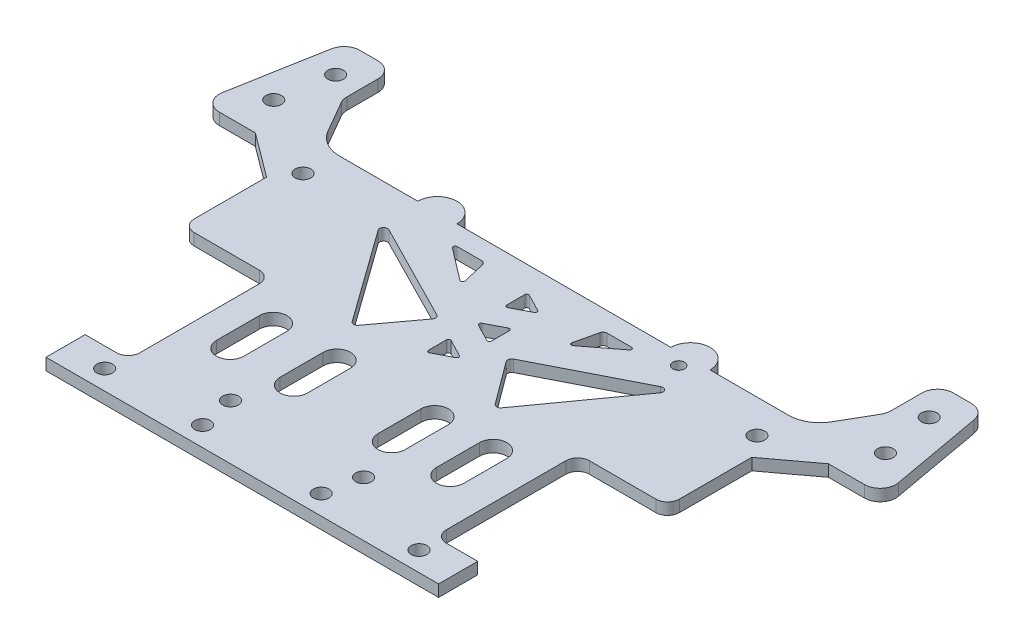
SolidWorks part; units mm, degrees
ref_plane "前视基准面" through (0, 0, 0) normal (0, 0, 1) x (1, 0, 0)
ref_plane "上视基准面" through (0, 0, 0) normal (0, 1, 0) x (1, 0, 0)
ref_plane "右视基准面" through (0, 0, 0) normal (1, 0, 0) x (0, 0, -1)
other "Configuration Table"
sketch "草图1" plane through (0, 0, 0) normal (0, 1, 0) x (1, 0, 0)
  line L0 (0, -16.9729) -> (0, 16.9729) construction
  line L1 (2, 16.9729) -> (2, -16.9729) construction
  line L3 (-2, 16.3622) -> (-2, -16.9729) construction
  point P3 (0, 0)
  dimension "D1" = 2
  dimension "D2" = 2
sketch "草图2" plane through (0, 0, 0) normal (0, 1, 0) x (1, 0, 0)
  line L0 (335.3431, 5) -> (-235.3431, 5) construction
  line L1 (-50, 0) -> (50, 0)
  line L2 (0, 0) -> (0, 19.5248) construction
  line L3 (42, 10) -> (50, 10)
  line L4 (50, 0) -> (50, 10)
  line L6 (0, 19.5248) -> (0, 40.19) construction
  line L8 (39, 13) -> (39, 43.53)
  line L9 (42, 46.53) -> (59, 46.53)
  line L10 (0, 40.19) -> (0, 82.03) construction
  line L11 (-57.3812, 82.03) -> (-37.34, 82.03)
  line L12 (62, 49.53) -> (62, 68.03)
  line L13 (64.3094, 86.03) -> (68.9641, 94.0922)
  line L14 (69.5, 96.0922) -> (69.5, 104.0204)
  line L17 (73.5, 108.0204) -> (78.1587, 108.0204)
  line L19 (82.0948, 104.7324) -> (86.3672, 81.1158)
  line L20 (62, 68.03) -> (73.2197, 76.4037)
  line L21 (73.2197, 76.4037) -> (82.4311, 76.4037)
  line L22 (12.5, 25.5) -> (12.5, 36.5) construction
  line L23 (9, 25.5) -> (9, 36.5)
  line L24 (16, 25.5) -> (16, 36.5)
  line L25 (-73.5, 108.0204) -> (-78.1587, 108.0204)
  line L26 (-69.5, 96.0922) -> (-69.5, 104.0204)
  line L27 (-64.3094, 86.03) -> (-68.9641, 94.0922)
  line L29 (-42.32, 10) -> (-50.32, 10)
  line L30 (-39.32, 13) -> (-39.32, 43.53)
  line L31 (-42.32, 46.53) -> (-59, 46.53)
  line L32 (-62, 49.53) -> (-62, 68.03)
  line L33 (-62, 68.03) -> (-73.2197, 76.4037)
  line L34 (-73.2197, 76.4037) -> (-82.4311, 76.4037)
  line L35 (-82.0948, 104.7324) -> (-86.3672, 81.1158)
  line L36 (-12.5, 25.5) -> (-12.5, 36.5) construction
  line L37 (-9, 25.5) -> (-9, 36.5)
  line L38 (-16, 25.5) -> (-16, 36.5)
  line L39 (-50.32, 10) -> (-50.32, 0)
  line L40 (-50, 0) -> (-50.32, 0)
  line L41 (-28.772, 36.5) -> (-28.772, 25.5) construction
  line L42 (-25.272, 36.5) -> (-25.272, 25.5)
  line L43 (-32.272, 36.5) -> (-32.272, 25.5)
  line L45 (27.4578, 36.5) -> (27.4578, 25.5) construction
  line L46 (30.9578, 36.5) -> (30.9578, 25.5)
  line L47 (23.9578, 36.5) -> (23.9578, 25.5)
  line L60 (-34.7339, 72.03) -> (-9.7834, 59.3228)
  line L61 (-9.4337, 57.8365) -> (-17.4687, 46.9881)
  line L62 (-19.0845, 47) -> (-36, 70.5556)
  line L63 (-22.2986, 77.03) -> (-15.9986, 77.03)
  line L64 (-15.0247, 76.2572) -> (-13.6616, 70.4141)
  line L65 (-14.4522, 69.9032) -> (-22.6022, 76.1328)
  line L66 (9.4337, 57.8365) -> (17.4687, 46.9881)
  line L67 (19.0845, 47) -> (36, 70.5556)
  line L68 (34.7339, 72.03) -> (9.7834, 59.3228)
  line L69 (14.4522, 69.9032) -> (22.6022, 76.1328)
  line L70 (15.0247, 76.2572) -> (13.6616, 70.4141)
  line L71 (22.2986, 77.03) -> (15.9986, 77.03)
  line L72 (-3.0133, 75.03) -> (-3.0133, 70.43)
  line L73 (-2.2833, 69.986) -> (2.1563, 72.286)
  line L74 (2.1563, 73.174) -> (-2.2833, 75.474)
  line L75 (3.0133, 65.0858) -> (3.0133, 60.4858)
  line L76 (2.2833, 60.0419) -> (-2.1563, 62.3419)
  line L77 (-2.1563, 63.2298) -> (2.2833, 65.5298)
  line L81 (-2.2833, 49.986) -> (2.1563, 52.286)
  line L82 (-3.0133, 55.03) -> (-3.0133, 50.43)
  line L83 (2.1563, 53.174) -> (-2.2833, 55.474)
  line L84 (32.34, 79) -> (32.34, 82.03) construction
  line L87 (-27.34, 82.03) -> (27.34, 82.03)
  line L88 (37.34, 82.03) -> (57.3812, 82.03)
  arc A0 (82.4311, 76.4037) -> (86.3672, 81.1158) centre (82.4311, 80.4037) ccw
  arc A1 (82.0948, 104.7324) -> (78.1587, 108.0204) centre (78.1587, 104.0204) ccw
  arc A2 (69.5, 104.0204) -> (73.5, 108.0204) centre (73.5, 104.0204) cw
  arc A3 (68.9641, 94.0922) -> (69.5, 96.0922) centre (65.5, 96.0922) ccw
  arc A4 (64.3094, 86.03) -> (57.3812, 82.03) centre (57.3812, 90.03) cw
  circle A5 centre (40, 5) radius 2
  circle A6 centre (15, 5) radius 2
  circle A7 centre (57.84, 73.5) radius 2
  circle A8 centre (16.84, 14) radius 2
  arc A9 (9, 25.5) -> (16, 25.5) centre (12.5, 25.5) ccw
  arc A10 (16, 36.5) -> (9, 36.5) centre (12.5, 36.5) ccw
  circle A11 centre (78.1587, 86.03) radius 2
  circle A12 centre (75.8293, 99.5272) radius 2
  arc A13 (-69.5, 104.0204) -> (-73.5, 108.0204) centre (-73.5, 104.0204) ccw
  arc A14 (-68.9641, 94.0922) -> (-69.5, 96.0922) centre (-65.5, 96.0922) cw
  arc A15 (-64.3094, 86.03) -> (-57.3812, 82.03) centre (-57.3812, 90.03) ccw
  arc A16 (-82.4311, 76.4037) -> (-86.3672, 81.1158) centre (-82.4311, 80.4037) cw
  arc A17 (-82.0948, 104.7324) -> (-78.1587, 108.0204) centre (-78.1587, 104.0204) cw
  circle A18 centre (-75.8293, 99.5272) radius 2
  circle A19 centre (-78.1587, 86.03) radius 2
  circle A20 centre (-58.16, 73.5) radius 2
  circle A21 centre (-40.32, 5) radius 2
  circle A22 centre (-15.32, 5) radius 2
  arc A24 (-9, 25.5) -> (-16, 25.5) centre (-12.5, 25.5) cw
  arc A25 (-16, 36.5) -> (-9, 36.5) centre (-12.5, 36.5) cw
  circle A26 centre (-17.16, 14) radius 2
  arc A27 (-59, 46.53) -> (-62, 49.53) centre (-59, 49.53) cw
  arc A28 (-39.32, 13) -> (-42.32, 10) centre (-42.32, 13) cw
  arc A29 (-42.32, 46.53) -> (-39.32, 43.53) centre (-42.32, 43.53) cw
  arc A30 (39, 43.53) -> (42, 46.53) centre (42, 43.53) cw
  arc A31 (59, 46.53) -> (62, 49.53) centre (59, 49.53) ccw
  arc A32 (42, 10) -> (39, 13) centre (42, 13) cw
  arc A33 (-25.272, 36.5) -> (-32.272, 36.5) centre (-28.772, 36.5) ccw
  arc A34 (-32.272, 25.5) -> (-25.272, 25.5) centre (-28.772, 25.5) ccw
  arc A35 (30.9578, 36.5) -> (23.9578, 36.5) centre (27.4578, 36.5) ccw
  arc A36 (23.9578, 25.5) -> (30.9578, 25.5) centre (27.4578, 25.5) ccw
  arc A37 (-34.7339, 72.03) -> (-36, 70.5556) centre (-35.1877, 71.1389) ccw
  arc A38 (-9.7834, 59.3228) -> (-9.4337, 57.8365) centre (-10.2372, 58.4317) cw
  arc A39 (-17.4687, 46.9881) -> (-19.0845, 47) centre (-18.2723, 47.5833) cw
  arc A40 (-15.9986, 77.03) -> (-15.0247, 76.2572) centre (-15.9986, 76.03) cw
  arc A41 (-22.2986, 77.03) -> (-22.6022, 76.1328) centre (-22.2986, 76.53) ccw
  arc A42 (-13.6616, 70.4141) -> (-14.4522, 69.9032) centre (-14.1486, 70.3005) cw
  arc A43 (9.7834, 59.3228) -> (9.4337, 57.8365) centre (10.2372, 58.4317) ccw
  arc A44 (17.4687, 46.9881) -> (19.0845, 47) centre (18.2723, 47.5833) ccw
  arc A45 (34.7339, 72.03) -> (36, 70.5556) centre (35.1877, 71.1389) cw
  arc A46 (22.2986, 77.03) -> (22.6022, 76.1328) centre (22.2986, 76.53) cw
  arc A47 (13.6616, 70.4141) -> (14.4522, 69.9032) centre (14.1486, 70.3005) ccw
  arc A48 (15.9986, 77.03) -> (15.0247, 76.2572) centre (15.9986, 76.03) ccw
  arc A49 (2.1563, 52.286) -> (2.1563, 53.174) centre (1.9263, 52.73) ccw
  arc A50 (-2.2833, 49.986) -> (-3.0133, 50.43) centre (-2.5133, 50.43) cw
  arc A51 (-3.0133, 55.03) -> (-2.2833, 55.474) centre (-2.5133, 55.03) cw
  arc A52 (3.0133, 60.4858) -> (2.2833, 60.0419) centre (2.5133, 60.4858) cw
  arc A53 (3.0133, 65.0858) -> (2.2833, 65.5298) centre (2.5133, 65.0858) ccw
  arc A54 (-2.1563, 62.3419) -> (-2.1563, 63.2298) centre (-1.9263, 62.7858) cw
  arc A55 (2.1563, 72.286) -> (2.1563, 73.174) centre (1.9263, 72.73) ccw
  arc A56 (-3.0133, 70.43) -> (-2.2833, 69.986) centre (-2.5133, 70.43) ccw
  arc A57 (-3.0133, 75.03) -> (-2.2833, 75.474) centre (-2.5133, 75.03) cw
  circle A58 centre (32.34, 79) radius 1.5
  arc A59 (27.34, 82.03) -> (37.34, 82.03) centre (32.34, 82.03) cw
  arc A60 (-27.34, 82.03) -> (-37.34, 82.03) centre (-32.34, 82.03) ccw
  point P11 (62, 68.03)
  point P14 (50, 5)
  point P29 (87.2197, 76.4037)
  point P33 (81.5, 108.0204)
  point P36 (69.5, 108.0204)
  point P39 (69.5, 95.0204)
  point P42 (62, 82.03)
  point P44 (12.5, 31)
  point P51 (12.5, 40)
  point P52 (12.5, 22)
  point P57 (-46.32, 10)
  point P58 (-69.5, 100.0563)
  point P64 (75.8293, 108.0204)
  point P79 (-39.32, 10)
  point P101 (-12.5, 31)
  point P111 (39, 46.53)
  point P114 (62, 46.53)
  point P117 (39, 10)
  point P120 (-28.772, 31)
  point P127 (27.4578, 31)
  point P178 (-3.0133, 72.73)
  point P180 (3.0133, 62.7858)
  point P195 (-3.0133, 62.7858)
  point P198 (3.0133, 72.73)
  dimension "D15" = 4
  dimension "D16" = 4
  dimension "D17" = 4
  dimension "D18" = 8
  dimension "D19" = 4
  dimension "D20" = 4
  dimension "D25" = 4
  dimension "D26" = 4
  dimension "D31" = 40
  dimension "D33" = 4
  dimension "D34" = 4
  dimension "D35" = 6.3293
  dimension "D36" = 8.4931
  dimension "D39" = 4
  dimension "D42" = 22.16
  dimension "D47" = 116
  dimension "D48" = 59.5
  dimension "D49" = 4
  dimension "D50" = 5
  dimension "D51" = 4
  dimension "D52" = 35
  dimension "D53" = 5
  dimension "D54" = 10
  dimension "D55" = 4
  dimension "D24" = 59.5
  dimension "D23" = 41
  dimension "D56" = 14
  dimension "D61" = 4
  dimension "D62" = 4
  dimension "D63" = 4
  dimension "D64" = 24
  dimension "D65" = 2.9037
  dimension "D66" = 9.6263
  dimension "D70" = 8
  dimension "D71" = 4
  dimension "D58" = 4
  dimension "D72" = 4
  dimension "D74" = 8.4931
  dimension "D67" = 8.6587
  dimension "D73" = 6.3293
  dimension "D75" = 3
  dimension "D76" = 3
  dimension "D77" = 3
  dimension "D80" = 11.5
  dimension "D81" = 22.5
  dimension "D85" = 25.5
  dimension "D86" = 1
  dimension "D87" = 1
  dimension "D88" = 1
  dimension "D89" = 1
  dimension "D90" = 0.5
  dimension "D91" = 0.5
  dimension "D92" = 0.5
  dimension "D109" = 3
  dimension "D112" = 5
  dimension "D1" = 50
  dimension "D2" = 10
  dimension "D3" = 36.53
  dimension "D4" = 39
  dimension "D5" = 62
  dimension "D6" = 35.5
  dimension "D7" = 14
  dimension "D8" = 15
  dimension "D9" = 14
  dimension "D10" = 14
  dimension "D11" = 60
  dimension "D12" = 15
  dimension "D13" = 13
  dimension "D14" = 12
  dimension "D21" = 10
  dimension "D22" = 24
  dimension "D27" = 4
  dimension "D28" = 22.16
  dimension "D29" = 30
  dimension "D30" = 23
  dimension "D32" = 22
  dimension "D37" = 9.6263
  dimension "D38" = 8.6587
  dimension "D40" = 34
  dimension "D41" = 14
  dimension "D43" = 36.53
  dimension "D44" = 124
  dimension "D45" = 11
  dimension "D46" = 10
  dimension "D57" = 9.2114
  dimension "D59" = 4.6587
  dimension "D60" = 7.9282
  dimension "D68" = 60
  dimension "D69" = 9.3094
  dimension "D78" = 25
  dimension "D79" = 8.16
  dimension "D82" = 31
  dimension "D83" = 8.0422
  dimension "D84" = 14.048
  dimension "D93" = 6.3
  dimension "D94" = 8.15
  dimension "D95" = 13.6616
  dimension "D96" = 5
  dimension "D97" = 10.2581
  dimension "D98" = 29
  dimension "D99" = 28
  dimension "D100" = 13.5
  dimension "D101" = 10
  dimension "D102" = 26
  dimension "D103" = 47
  dimension "D104" = 4.6
  dimension "D105" = 5
  dimension "D106" = 7
  dimension "D107" = 18.8002
  dimension "D108" = 27
  dimension "D110" = 25.5
  dimension "D111" = 5.5
extrude "凸台-拉伸2" add sketch "草图2" along normal blind 3
